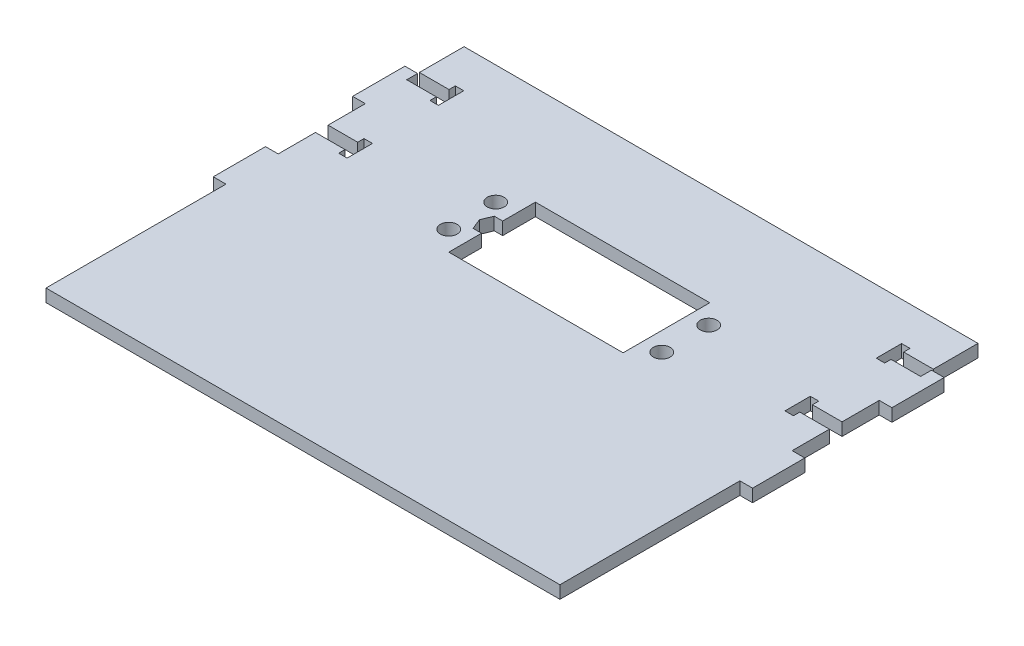
SolidWorks part; units mm, degrees
material "Balsa"
ref_plane "Front" through (0, 0, 0) normal (0, 0, 1) x (1, 0, 0)
ref_plane "Top" through (0, 0, 0) normal (0, 1, 0) x (1, 0, 0)
ref_plane "Right" through (0, 0, 0) normal (1, 0, 0) x (0, 0, -1)
sketch "Sketch2" plane through (0, 0, 0) normal (0, 1, 0) x (1, 0, 0)
  line L0 (0, 0) -> (0, 20.5)
  line L1 (0, 20.5) -> (-9, 20.5)
  line L2 (-9, 20.5) -> (-9, -55)
  line L3 (-9, -55) -> (50, -55)
  line L4 (50, -55) -> (50, 20.5)
  line L5 (50, 20.5) -> (41.25, 20.5)
  line L6 (41.25, 20.5) -> (41.25, 0)
  line L7 (41.25, 0) -> (0, 0)
  line L8 (0, 10.25) -> (-3, 10.25) construction
  line L9 (-3, 10.25) -> (-2, 12.75)
  line L10 (-2, 12.75) -> (0, 12.75)
  line L11 (-2, 7.75) -> (0, 7.75)
  line L12 (-3, 10.25) -> (-2, 7.75)
  line L13 (-40.3, 20.5) -> (-40.3, 43.9197)
  line L14 (-40.3, 43.9197) -> (81.3, 43.9197)
  line L15 (81.3, 43.9197) -> (81.3, 20.5)
  line L16 (0, 20.5) -> (41.25, 20.5)
  line L17 (48.5, 20.5) -> (41, 20.5) construction
  line L19 (-9, 20.5) -> (-40.3, 20.5)
  line L20 (-9, 20.5) -> (-9, -55)
  line L21 (-9, -55) -> (-40.3, -55)
  line L22 (-40.3, 20.5) -> (-40.3, -55)
  line L23 (50, 20.5) -> (81.3, 20.5)
  line L24 (50, 20.5) -> (50, -55)
  line L25 (-7.5, 16.965) -> (-7.5, 20.5) construction
  line L26 (48.5, 16.965) -> (48.5, 20.5) construction
  line L27 (50, -55) -> (81.3, -55)
  line L28 (81.3, 20.5) -> (81.3, -55)
  circle A4 centre (-4.7, 15.8) radius 2
  arc A5 (-6.3257, 14.635) -> (-6.3257, 16.965) centre (-4.7, 15.8) ccw construction
  circle A6 centre (-4.7, 4.7) radius 2
  circle A7 centre (45.7, 4.7) radius 2
  circle A8 centre (45.7, 15.8) radius 2
  point P29 (-40.1343, 69.623)
  point P30 (-40.0131, 40.891)
  point P40 (-40.6193, 46.5889)
  point P41 (-40.0127, 43.9197)
  dimension "D1" = 41.25
  dimension "D2" = 1.5
  dimension "D3" = 1.5
  dimension "D4" = 55
  dimension "D5" = 2.5
  dimension "D6" = 3
  dimension "D7" = 2
  dimension "D8" = 121.6
extrude "Boss-Extrude1" add sketch "Sketch2" along normal blind 3 contours L19 L22 L21 L2 | L6 L7 L0 L1 L2 L3 L4 L5 A8 A7 A6 A4 | L28 L23 L4 L27 | L5 L23 L15 L14 L13 L19 L1 L16
sketch "Sketch3" plane through (0, 0, 0) normal (0, 1, 0) x (1, 0, 0)
  line L0 (-40.3, 43.9197) -> (-40.3, -55) construction
  line L1 (-40.3, 32.9191) -> (-43.3, 32.9191)
  line L2 (-43.3, 32.9191) -> (-43.3, 20.5541)
  line L3 (-43.3, 20.5541) -> (-40.3, 20.5541)
  line L4 (-40.3, 10.25) -> (41.25, 10.25) construction
  line L5 (-40.3, 20.5541) -> (-40.3, 32.9191)
  line L6 (-43.3, -0.0541) -> (-40.3, -0.0541)
  line L7 (-43.3, -12.4191) -> (-43.3, -0.0541)
  line L8 (-40.3, -12.4191) -> (-43.3, -12.4191)
  line L9 (-40.3, -0.0541) -> (-40.3, -12.4191)
  line L10 (20.5, -55) -> (20.5, 43.9197) construction
  line L11 (81.3, -55) -> (-40.3, -55) construction
  line L12 (-40.3, 43.9197) -> (81.3, 43.9197) construction
  line L13 (81.3, -0.0541) -> (81.3, -12.4191)
  line L14 (81.3, -12.4191) -> (84.3, -12.4191)
  line L15 (84.3, -12.4191) -> (84.3, -0.0541)
  line L16 (84.3, -0.0541) -> (81.3, -0.0541)
  line L17 (81.3, 20.5541) -> (81.3, 32.9191)
  line L18 (84.3, 20.5541) -> (81.3, 20.5541)
  line L19 (84.3, 32.9191) -> (84.3, 20.5541)
  line L20 (81.3, 32.9191) -> (84.3, 32.9191)
  line L21 (41.25, 20.5) -> (41.25, 0) construction
  point P10 (-43.3, 26.7366)
  point P29 (84.3, 26.7366)
  point P30 (41.25, 10.25)
  dimension "D1" = 98.9197
  dimension "D2" = 16.4866
  dimension "D3" = 12.365
  dimension "D4" = 3
extrude "Boss-Extrude2" add sketch "Sketch3" along normal through all
sketch "Sketch4" plane through (0, 0, 0) normal (0, 1, 0) x (1, 0, 0)
  line L1 (81.3, 20.5541) -> (81.3, -0.0541) construction
  line L3 (81.3, 43.9197) -> (81.3, 32.9191) construction
  line L5 (81.3, 8.75) -> (74.3, 8.75)
  line L6 (74.3, 8.75) -> (74.3, 7.25)
  line L7 (74.3, 7.25) -> (72.3, 7.25)
  line L8 (72.3, 7.25) -> (72.3, 13.25)
  line L9 (72.3, 13.25) -> (74.3, 13.25)
  line L10 (74.3, 13.25) -> (74.3, 11.75)
  line L11 (81.3, 11.75) -> (74.3, 11.75)
  line L12 (81.3, 30.3485) -> (74.3, 30.3485)
  line L13 (74.3, 30.3485) -> (74.3, 28.8485)
  line L14 (74.3, 28.8485) -> (72.3, 28.8485)
  line L15 (72.3, 28.8485) -> (72.3, 34.8485)
  line L16 (72.3, 34.8485) -> (74.3, 34.8485)
  line L17 (74.3, 34.8485) -> (74.3, 33.3485)
  line L18 (74.3, 33.3485) -> (81.3, 33.3485)
  line L21 (84.3, 33.3485) -> (81.3, 33.3485) construction
  line L22 (20.5, 43.9197) -> (20.5, -55) construction
  line L23 (-40.3, 43.9197) -> (81.3, 43.9197) construction
  line L24 (81.3, -55) -> (-40.3, -55) construction
  line L25 (81.3, 8.75) -> (81.3, 11.75)
  line L26 (81.3, 30.3485) -> (81.3, 33.3485)
  line L27 (-40.3, 30.3485) -> (-40.3, 33.3485)
  line L28 (-40.3, 8.75) -> (-40.3, 11.75)
  line L29 (-33.3, 33.3485) -> (-40.3, 33.3485)
  line L30 (-33.3, 34.8485) -> (-33.3, 33.3485)
  line L31 (-31.3, 34.8485) -> (-33.3, 34.8485)
  line L32 (-31.3, 28.8485) -> (-31.3, 34.8485)
  line L33 (-33.3, 28.8485) -> (-31.3, 28.8485)
  line L34 (-33.3, 30.3485) -> (-33.3, 28.8485)
  line L35 (-40.3, 30.3485) -> (-33.3, 30.3485)
  line L36 (-40.3, 11.75) -> (-33.3, 11.75)
  line L37 (-33.3, 13.25) -> (-33.3, 11.75)
  line L38 (-31.3, 13.25) -> (-33.3, 13.25)
  line L39 (-31.3, 7.25) -> (-31.3, 13.25)
  line L40 (-33.3, 7.25) -> (-31.3, 7.25)
  line L41 (-33.3, 8.75) -> (-33.3, 7.25)
  line L42 (-40.3, 8.75) -> (-33.3, 8.75)
  point P0 (81.3, 8.75)
  point P1 (81.3, 11.75)
  point P6 (81.3, 30.3485)
  point P9 (81.3, 33.3485)
  dimension "D1" = 9
  dimension "D2" = 2
  dimension "D3" = 6
extrude "Cut-Extrude1" cut sketch "Sketch4" along normal through all
sketch "Sketch5" plane through (0, 3, 0) normal (0, 1, 0) x (1, 0, 0)
  text T0 "side a"
equation "\"D2@Sketch3\"=\"D1@Sketch3\"/6"
equation "\"D3@Sketch3\"=\"D1@Sketch3\"/8"
